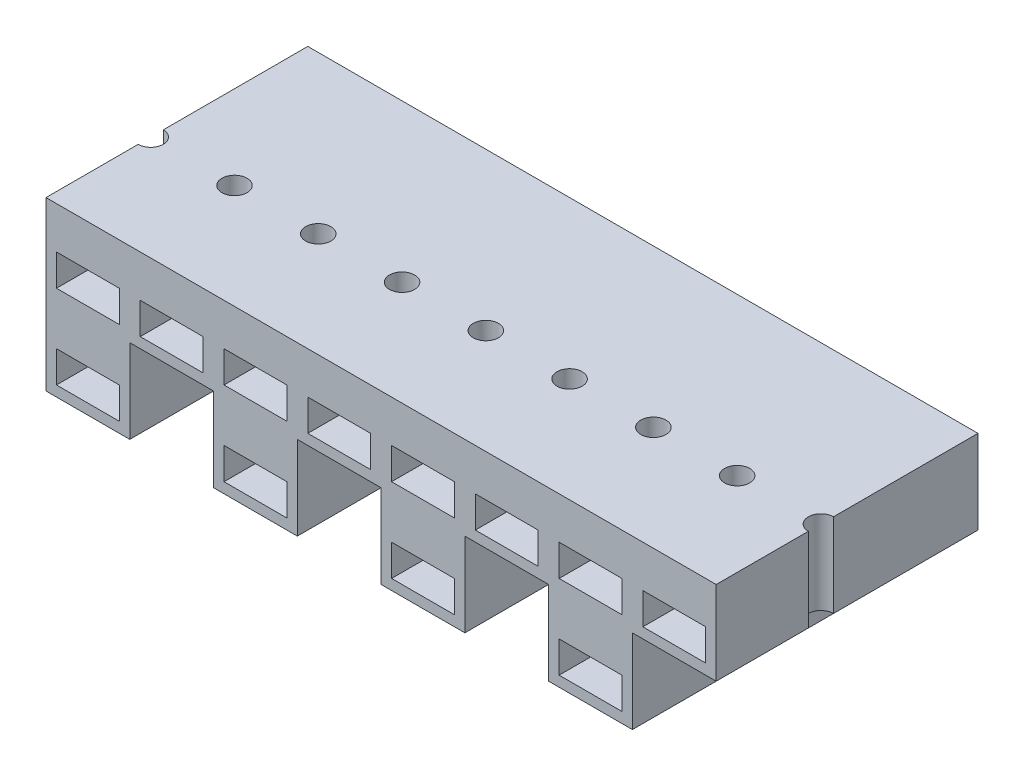
SolidWorks part; units mm, degrees
ref_plane "Front Plane" through (0, 0, 0) normal (0, 0, 1) x (1, 0, 0)
ref_plane "Top Plane" through (0, 0, 0) normal (0, 1, 0) x (1, 0, 0)
ref_plane "Right Plane" through (0, 0, 0) normal (1, 0, 0) x (0, 0, -1)
sketch "Sketch1" plane through (0, 0, 0) normal (0, 0, 1) x (1, 0, 0)
  line L0 (-32, 0) -> (32, 0)
  line L1 (32, 0) -> (32, -8)
  line L2 (32, -8) -> (24, -8)
  line L3 (24, -8) -> (24, -16)
  line L4 (24, -16) -> (16, -16)
  line L5 (16, -16) -> (16, -8)
  line L6 (16, -8) -> (8, -8)
  line L7 (8, -8) -> (8, -16)
  line L8 (8, -16) -> (0, -16)
  line L9 (0, -16) -> (0, -8)
  line L10 (0, -8) -> (-8, -8)
  line L11 (-8, -8) -> (-8, -16)
  line L12 (-8, -16) -> (-16, -16)
  line L13 (-16, -16) -> (-16, -8)
  line L14 (-16, -8) -> (-24, -8)
  line L15 (-24, -8) -> (-24, -16)
  line L16 (-24, -16) -> (-32, -16)
  line L17 (-32, -16) -> (-32, 0)
  dimension "D1" = 64
  dimension "D2" = 8
  dimension "D3" = 8
extrude "Boss-Extrude1" add sketch "Sketch1" along normal blind 10 and the other way blind 15
sketch "Sketch2" plane through (0, 0, 0) normal (0, 1, 0) x (1, 0, 0)
  line L0 (-32, 15) -> (-32, -10) construction
  circle A0 centre (-32, 0) radius 1.2
  dimension "D1" = 2.4
extrude "Cut-Extrude1" cut sketch "Sketch2" against normal through all
pattern_linear "LPattern1" count 9 spacing 8 along (1, 0, 0) of "Cut-Extrude1"
sketch "Sketch3" plane through (0, 0, 10) normal (0, 0, 1) x (1, 0, 0)
  line L0 (-31, -4) -> (-31, -7)
  line L1 (-31, -4) -> (-25, -4)
  line L2 (-31, -7) -> (-25, -7)
  line L3 (-25, -4) -> (-25, -7)
  line L4 (-32, -4) -> (-31, -4) construction
  line L5 (-32, 0) -> (-32, -16) construction
  line L6 (32, 0) -> (-32, 0) construction
  line L8 (-24, -8) -> (-24, -7) construction
  line L9 (-24, -7) -> (-25, -7) construction
  dimension "D1" = 4
  dimension "D2" = 6
extrude "Cut-Extrude2" cut sketch "Sketch3" against normal up to surface (10 mm away)
pattern_linear "LPattern2" count 8 spacing 8 along (1, 0, 0) count 2 spacing 8 along (0, -1, 0) of "Cut-Extrude2"
